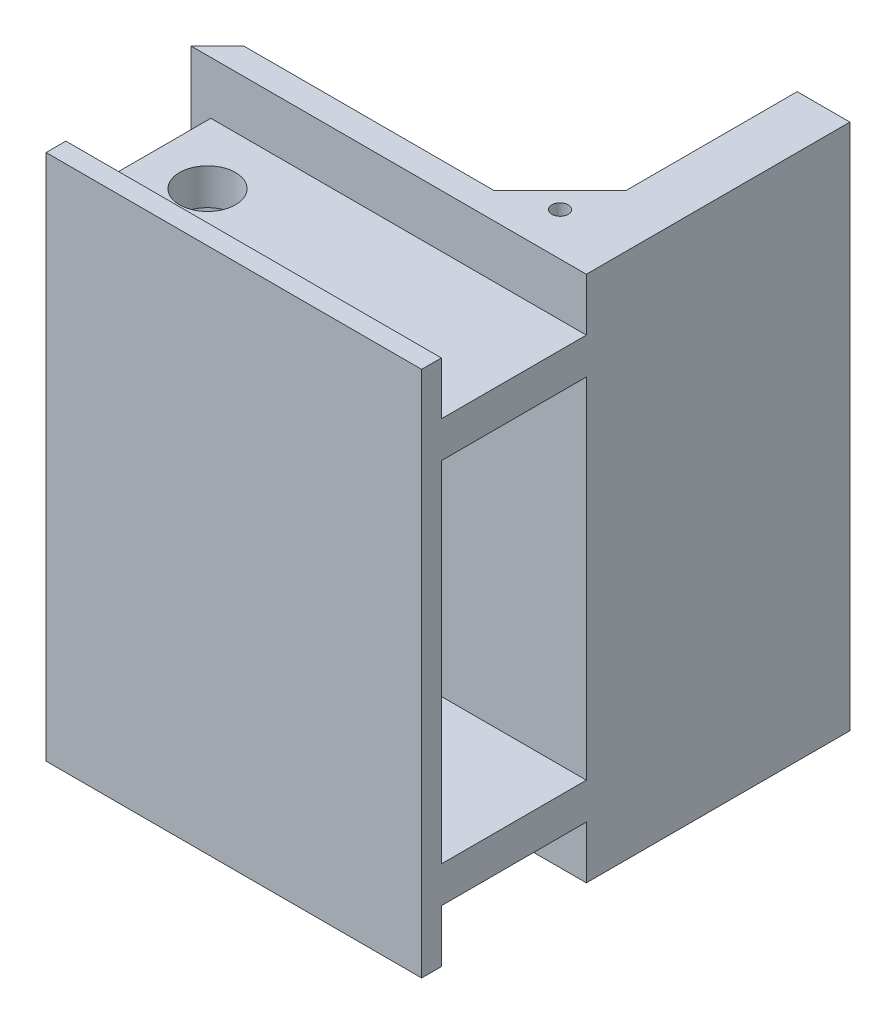
SolidWorks part; units mm, degrees
ref_plane "Front Plane" through (0, 0, 0) normal (0, 0, 1) x (1, 0, 0)
ref_plane "Top Plane" through (0, 0, 0) normal (0, 1, 0) x (1, 0, 0)
ref_plane "Right Plane" through (0, 0, 0) normal (1, 0, 0) x (0, 0, -1)
sketch "Sketch1" plane through (0, 0, 0) normal (0, 1, 0) x (1, 0, 0)
  line L0 (-17.3516, 20.3127) -> (-57.3516, -19.6873)
  line L1 (-17.3516, 20.3127) -> (2.6484, 20.3127)
  line L2 (-17.3516, 20.3127) -> (-17.3516, -19.6873)
  line L3 (-17.3516, -19.6873) -> (2.6484, -19.6873)
  line L4 (2.6484, 20.3127) -> (2.6484, -19.6873)
  line L5 (-57.3516, -19.6873) -> (-17.3516, -19.6873)
  dimension "D1" = 20
  dimension "D2" = 40
  dimension "D3" = 40
extrude "Boss-Extrude1" add sketch "Sketch1" against normal blind 80 contours L0 L5 L2 | L4 L1 L2 L3
sketch "Sketch8" plane through (2.6484, 0, 0) normal (1, 0, 0) x (0, 0, -1)
  line L0 (-19.6873, -80) -> (-19.6873, 0) construction
  line L14 (-19.6873, -8) -> (-44.6873, -8)
  line L15 (-19.6873, -8) -> (-19.6873, -72)
  line L16 (-19.6873, -72) -> (-44.6873, -72)
  line L17 (-44.6873, -8) -> (-44.6873, -72)
  dimension "D2" = 64
  dimension "D3" = 8
  dimension "D12" = 25
extrude "Boss-Extrude2" add sketch "Sketch8" against normal blind 57
sketch "Sketch12" plane through (0, -72, 0) normal (0, -1, 0) x (1, 0, 0)
  line L0 (2.6484, 44.6873) -> (2.6484, 19.6873) construction
  line L1 (-54.3516, 44.6873) -> (2.6484, 44.6873)
  line L2 (-54.3516, 44.6873) -> (-54.3516, 38.6873)
  line L3 (-54.3516, 38.6873) -> (2.6484, 38.6873)
  line L4 (2.6484, 44.6873) -> (2.6484, 38.6873)
  dimension "D1" = 6
extrude "Boss-Extrude3" add sketch "Sketch12" along normal blind 8
sketch "Sketch14" plane through (0, -8, 0) normal (0, 1, 0) x (1, 0, 0)
  line L0 (2.6484, -19.6873) -> (2.6484, -44.6873) construction
  line L1 (-54.3516, -44.6873) -> (2.6484, -44.6873)
  line L2 (-54.3516, -44.6873) -> (-54.3516, -38.6873)
  line L3 (-54.3516, -38.6873) -> (2.6484, -38.6873)
  line L4 (2.6484, -44.6873) -> (2.6484, -38.6873)
  dimension "D1" = 6
extrude "Boss-Extrude4" add sketch "Sketch14" along normal blind 8
sketch "Sketch17" plane through (0, 0, -20.3127) normal (0, 0, -1) x (-1, 0, 0)
  line L1 (5.3516, 0) -> (53.3516, 0)
  line L2 (5.3516, 0) -> (5.3516, -80)
  line L3 (5.3516, -80) -> (53.3516, -80)
  line L4 (53.3516, 0) -> (53.3516, -80)
  line L6 (57.3516, -80) -> (57.3516, 0) construction
  line L7 (-2.6484, -80) -> (-2.6484, 0) construction
  line L8 (17.3516, 0) -> (57.3516, 0) construction
  line L9 (17.3516, -80) -> (57.3516, -80) construction
  dimension "D3" = 4
  dimension "D4" = 8
extrude "Cut-Extrude4" cut sketch "Sketch17" against normal blind 36
chamfer "Chamfer1" distance 10 angle 45 1 edges at (-5.3516, -40, 15.6873)
sketch "Sketch16" plane through (0, 0, 15.6873) normal (0, 0, -1) x (-1, 0, 0)
  line L0 (53.3516, -80) -> (53.3516, 0) construction
  line L1 (53.3516, -76) -> (5.3516, -76)
  line L2 (53.3516, -76) -> (53.3516, -4)
  line L3 (53.3516, -4) -> (5.3516, -4)
  line L4 (5.3516, -76) -> (5.3516, -4)
  line L5 (5.3516, 0) -> (5.3516, -80) construction
  line L6 (53.3516, 0) -> (15.3516, 0) construction
  line L7 (15.3516, -80) -> (53.3516, -80) construction
  dimension "D1" = 4
  dimension "D2" = 4
extrude "Cut-Extrude5" cut sketch "Sketch16" along normal blind 10
sketch "Sketch19" plane through (0, 0, 0) normal (0, 1, 0) x (1, 0, 0)
  line L0 (-15.3516, -15.6873) -> (2.6484, -15.6873) construction
  line L1 (-5.3516, -5.6873) -> (-15.3516, -15.6873) construction
  line L2 (2.6484, 20.3127) -> (2.6484, -19.6873) construction
  line L3 (-5.3516, -5.6873) -> (-5.3516, -19.6873) construction
  line L4 (-57.3516, -19.6873) -> (2.6484, -19.6873) construction
  line L5 (-10.3516, -10.6873) -> (-5.3516, -15.6873) construction
  circle A0 centre (-7.8516, -13.1873) radius 1.25
  dimension "D1" = 2.5
extrude "Cut-Extrude6" cut sketch "Sketch19" against normal through all
sketch "Sketch21" plane through (-54.3516, 0, 0) normal (-1, 0, 0) x (0, 0, 1)
  line L0 (19.6873, -40) -> (38.6873, -40) construction
  line L1 (19.6873, -13.5) -> (38.6873, -13.5)
  line L2 (19.6873, -13.5) -> (19.6873, -66.5)
  line L3 (19.6873, -66.5) -> (38.6873, -66.5)
  line L4 (38.6873, -13.5) -> (38.6873, -66.5)
  line L8 (44.6873, -40) -> (19.6873, -40) construction
  line L9 (44.6873, 0) -> (44.6873, -80) construction
  line L10 (19.6873, -80) -> (19.6873, 0) construction
  dimension "D1" = 19
  dimension "D2" = 53
extrude "Cut-Extrude7" cut sketch "Sketch21" against normal through all
sketch "Sketch22" plane through (0, -72, 0) normal (0, -1, 0) x (1, 0, 0)
  line L0 (-54.3516, 29.1873) -> (2.6484, 29.1873) construction
  line L1 (-54.3516, 38.6873) -> (-54.3516, 19.6873) construction
  line L2 (2.6484, 38.6873) -> (2.6484, 19.6873) construction
  line L4 (-45.3516, 22.1873) -> (-54.3516, 22.1873)
  line L6 (2.6484, 44.6873) -> (-54.3516, 44.6873) construction
  line L7 (-54.3516, 38.6873) -> (2.6484, 38.6873) construction
  circle A0 centre (-45.3516, 29.1873) radius 4.25
  circle A2 centre (-45.3516, 29.1873) radius 7
  dimension "D1" = 8.5
  dimension "D2" = 14
  dimension "D3" = 9
extrude "Cut-Extrude8" cut sketch "Sketch22" against normal through all contours A0
sketch "Sketch25" plane through (-54.3516, 0, 0) normal (-1, 0, 0) x (0, 0, 1)
  line L0 (44.6873, -80) -> (38.6873, -80) construction
  line L1 (38.6873, -72) -> (41.6873, -72)
  line L2 (38.6873, -72) -> (38.6873, -80)
  line L3 (38.6873, -80) -> (41.6873, -80)
  line L4 (41.6873, -72) -> (41.6873, -80)
  line L5 (38.6873, 0) -> (44.6873, 0) construction
  line L6 (38.6873, -66.5) -> (41.6873, -66.5)
  line L7 (38.6873, -66.5) -> (38.6873, -13.5)
  line L8 (38.6873, -13.5) -> (41.6873, -13.5)
  line L9 (41.6873, -66.5) -> (41.6873, -13.5)
  line L10 (38.6873, -8) -> (41.6873, -8)
  line L11 (38.6873, -8) -> (38.6873, 0)
  line L12 (38.6873, 0) -> (41.6873, 0)
  line L13 (41.6873, -8) -> (41.6873, 0)
  line L14 (38.6873, -13.5) -> (19.6873, -13.5) construction
  dimension "D1" = 3
extrude "Cut-Extrude11" cut sketch "Sketch25" against normal through all
